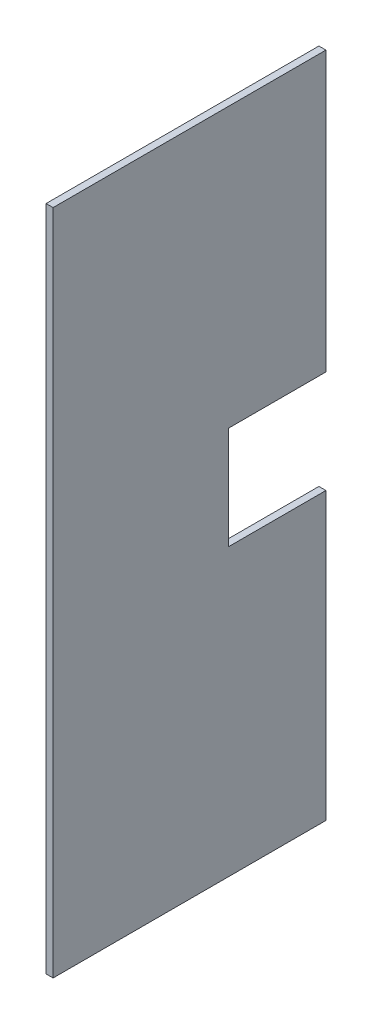
SolidWorks part; units mm, degrees
ref_plane "Спереди" through (0, 0, 0) normal (0, 0, 1) x (1, 0, 0)
ref_plane "Сверху" through (0, 0, 0) normal (0, 1, 0) x (1, 0, 0)
ref_plane "Справа" through (0, 0, 0) normal (1, 0, 0) x (0, 0, -1)
ref_plane "Плоскость4" through (0.5, 0, 0) normal (-1, 0, 0) x (0, -1, 0)
sketch "Эскиз1" plane through (0.5, 0, 0) normal (-1, 0, 0) x (0, -1, 0)
  line L0 (-5.85, 42.25) -> (-100.85, 42.25)
  line L1 (-100.85, 42.25) -> (-100.85, 3.4)
  line L2 (-100.85, 3.4) -> (-5.85, 3.4)
  line L3 (-5.85, 3.4) -> (-5.85, 42.25)
extrude "Бобышка-Вытянуть1" add sketch "Эскиз1" against normal blind 0.5
sketch "Эскиз2" plane through (0.5, 0, 0) normal (-1, 0, 0) x (0, 0, 1)
  line L0 (42.25, 5.85) -> (3.4, 5.85)
  line L1 (3.4, 5.85) -> (3.4, 100.85)
  line L2 (3.4, 100.85) -> (42.25, 100.85)
  line L3 (42.25, 100.85) -> (42.25, 5.85)
extrude "Бобышка-Вытянуть2" add sketch "Эскиз2" along normal blind 0.5
sketch "Эскиз3" plane through (0, 0, 0) normal (-1, 0, 0) x (0, 0, 1)
  line L1 (-5.3267, 46.5419) -> (17.3066, 46.5419)
  line L2 (-5.3267, 46.5419) -> (-5.3267, 61.1559)
  line L3 (-5.3267, 61.1559) -> (17.3066, 61.1559)
  line L4 (17.3066, 46.5419) -> (17.3066, 61.1559)
extrude "Вырез-Вытянуть1" cut sketch "Эскиз3" against normal through all
